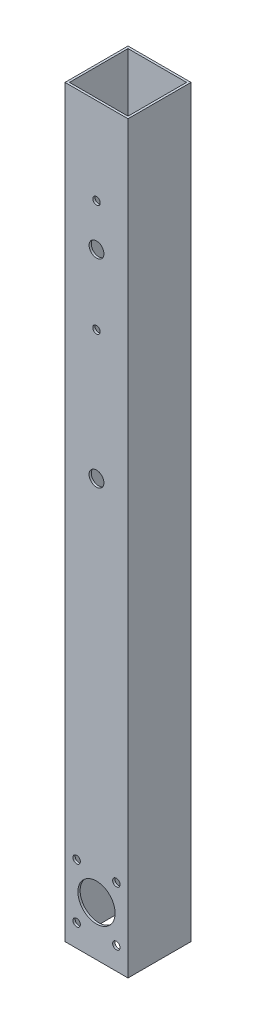
SolidWorks part; units mm, degrees
ref_plane "Front Plane" through (0, 0, 0) normal (0, 0, 1) x (1, 0, 0)
ref_plane "Top Plane" through (0, 0, 0) normal (0, 1, 0) x (1, 0, 0)
ref_plane "Right Plane" through (0, 0, 0) normal (1, 0, 0) x (0, 0, -1)
sketch "Sketch1" plane through (0, 0, 0) normal (0, 1, 0) x (1, 0, 0)
  line L0 (-11.8, 11.8) -> (-11.8, -11.8)
  line L1 (-12.7, 12.7) -> (12.7, 12.7)
  line L2 (-12.7, 12.7) -> (-12.7, -12.7)
  line L3 (-12.7, -12.7) -> (12.7, -12.7)
  line L4 (12.7, 12.7) -> (12.7, -12.7)
  line L5 (-12.7, 12.7) -> (12.7, -12.7) construction
  line L6 (-12.7, -12.7) -> (12.7, 12.7) construction
  line L7 (-11.8, -11.8) -> (11.8, -11.8)
  line L8 (11.8, 11.8) -> (11.8, -11.8)
  line L9 (-11.8, 11.8) -> (11.8, 11.8)
  point P0 (0, 0)
  dimension "D1" = 0.9
extrude "Boss-Extrude1" add sketch "Sketch1" along normal blind 300
sketch "Sketch2" plane through (0, 0, -12.7) normal (0, 0, -1) x (-1, 0, 0)
  circle A0 centre (0, 20) radius 7.5
extrude "Cut-Extrude1" cut sketch "Sketch2" against normal blind 25.4
sketch "Sketch3" plane through (0, 0, -12.7) normal (0, 0, -1) x (-1, 0, 0)
  circle A0 centre (0, 168) radius 3
  circle A1 centre (0, 248) radius 3
extrude "Cut-Extrude2" cut sketch "Sketch3" against normal blind 25.4
sketch "Sketch4" plane through (0, 0, -12.7) normal (0, 0, -1) x (-1, 0, 0)
  circle A1 centre (8, 9) radius 1.5
  circle A5 centre (8, 31) radius 1.5
  circle A6 centre (-8, 9) radius 1.5
  circle A7 centre (-8, 31) radius 1.5
extrude "Cut-Extrude3" cut sketch "Sketch4" against normal blind 25.4
sketch "Sketch5" plane through (0, 0, -12.7) normal (0, 0, -1) x (-1, 0, 0)
  circle A0 centre (0, 220) radius 1.5
  circle A1 centre (0, 265) radius 1.5
extrude "Cut-Extrude4" cut sketch "Sketch5" against normal blind 25.4
